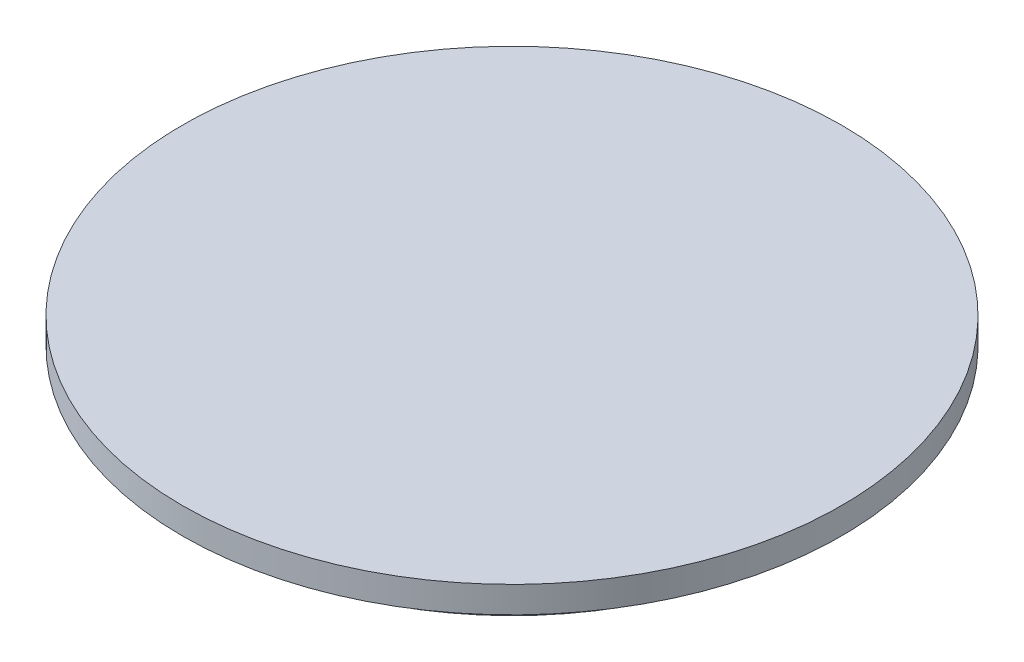
SolidWorks part; units mm, degrees
ref_plane "Plan de face" through (0, 0, 0) normal (0, 0, 1) x (1, 0, 0)
ref_plane "Plan de dessus" through (0, 0, 0) normal (0, 1, 0) x (1, 0, 0)
ref_plane "Plan de droite" through (0, 0, 0) normal (1, 0, 0) x (0, 0, -1)
sketch "Esquisse2" plane through (0, 0, 0) normal (0, 0, 1) x (1, 0, 0)
  line L0 (0, 0) -> (8.9, 0)
  line L1 (8.9, 0) -> (8.9, 0.8)
  line L2 (8.9, 0.8) -> (10, 0.8)
  line L3 (10, 0.8) -> (10, 1.6)
  line L4 (10, 1.6) -> (0, 1.6)
  line L5 (0, 1.6) -> (0, 0)
  dimension "D1" = 8.9
  dimension "D2" = 10
  dimension "D3" = 0.8
  dimension "D4" = 0.8
revolve "Révolution1" add sketch "Esquisse2" angle 360 about L5
